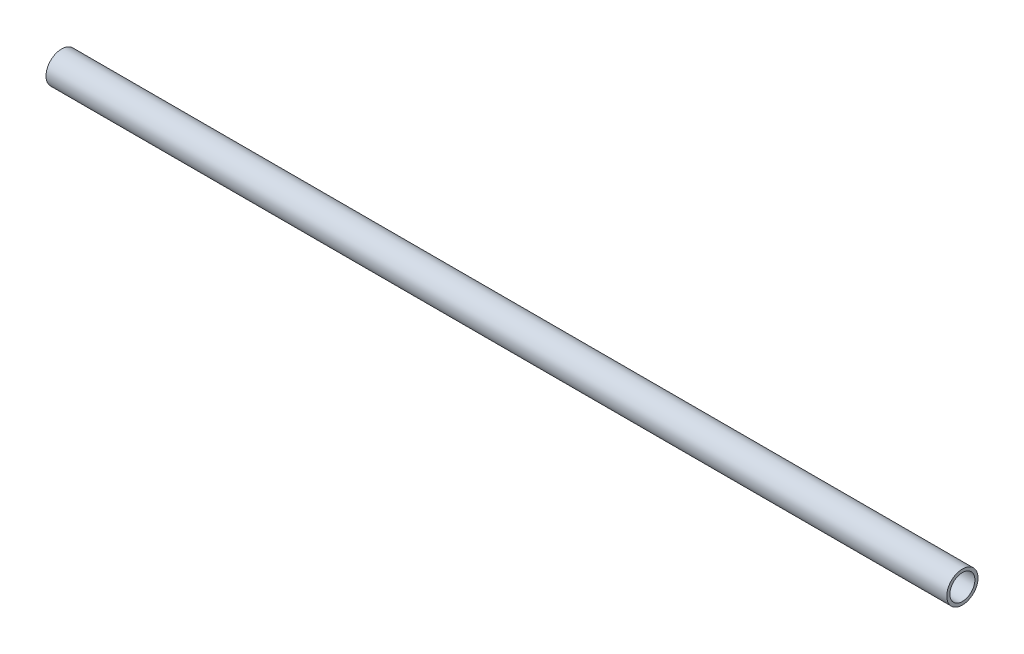
SolidWorks part; units mm, degrees
ref_plane "Front Plane" through (0, 0, 0) normal (0, 0, 1) x (1, 0, 0)
ref_plane "Top Plane" through (0, 0, 0) normal (0, 1, 0) x (1, 0, 0)
ref_plane "Right Plane" through (0, 0, 0) normal (1, 0, 0) x (0, 0, -1)
sketch "Sketch1" plane through (0, 0, 0) normal (0, 0, 1) x (1, 0, 0)
  line L2 (457.2, 15.875) -> (-457.2, 15.875)
  line L4 (-444.7827, 0) -> (543.3428, 0) construction
  line L5 (-457.2, 15.875) -> (-457.2, 12.7)
  line L6 (-457.2, 12.7) -> (457.2, 12.7)
  line L7 (457.2, 12.7) -> (457.2, 15.875)
  point P0 (0, 15.875)
  dimension "D1" = 914.4
  dimension "D2" = 31.75
  dimension "D3" = 3.175
revolve "Revolve1" add sketch "Sketch1" angle 360 about L4
sketch "Sketch2" [suppressed] plane through (0, 0, 0) normal (0, 1, 0) x (1, 0, 0)
  line L5 (457.2, -15.875) -> (457.2, 15.875) construction
  circle A0 centre (355.6, 0) radius 6.35
  dimension "D1" = 12.7
  dimension "D2" = 101.6
extrude "Cut-Extrude1" [suppressed] cut sketch "Sketch2" against normal through all and the other way through all
